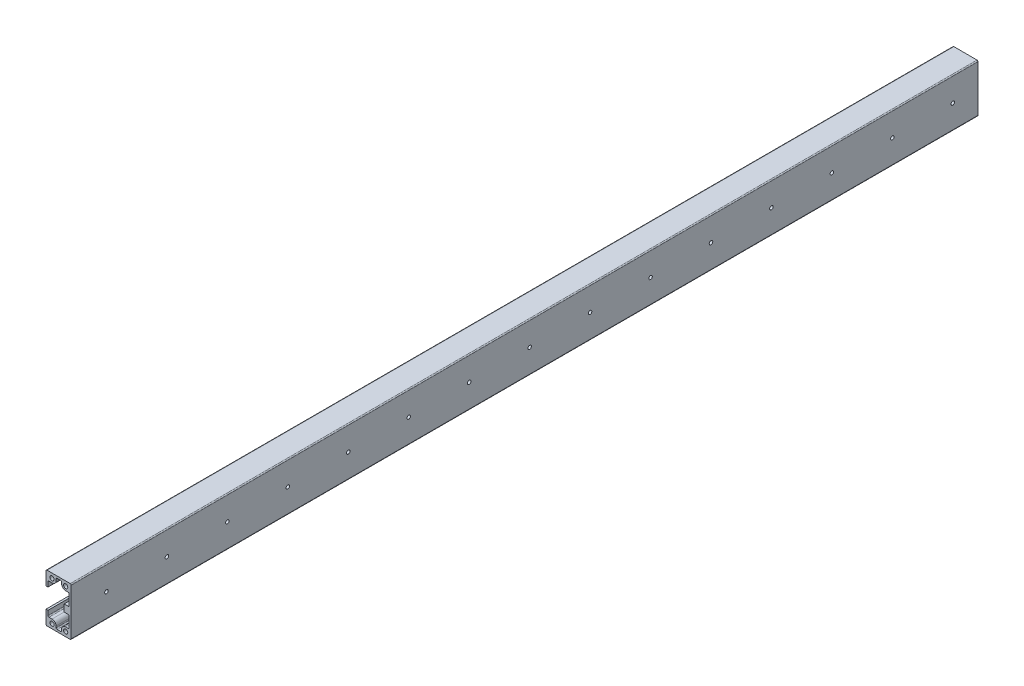
SolidWorks part; units mm, degrees
ref_plane "前视基准面" through (0, 0, 0) normal (0, 0, 1) x (1, 0, 0)
ref_plane "上视基准面" through (0, 0, 0) normal (0, 1, 0) x (1, 0, 0)
ref_plane "右视基准面" through (0, 0, 0) normal (1, 0, 0) x (0, 0, -1)
sketch "草图1" plane through (0, 0, 0) normal (0, 0, 1) x (1, 0, 0)
  line L95 (1744.9386, 1131.7125) -> (1767.9386, 1131.7125)
  line L96 (1768.9386, 1132.7125) -> (1768.9386, 1178.7125)
  line L97 (1767.9386, 1179.7125) -> (1744.9386, 1179.7125)
  line L98 (1743.9386, 1132.7125) -> (1743.9386, 1178.7125)
  line L99 (1754.9386, 1133.7125) -> (1758.4386, 1133.7125)
  line L100 (1745.9386, 1141.2125) -> (1745.9386, 1170.2125)
  line L101 (1766.9386, 1140.2125) -> (1766.9386, 1151.2125)
  line L102 (1765.9386, 1152.2125) -> (1761.9386, 1152.2125)
  line L103 (1765.9386, 1159.2125) -> (1761.9386, 1159.2125)
  line L104 (1761.9386, 1152.2125) -> (1761.9386, 1159.2125)
  line L105 (1766.9386, 1160.2125) -> (1766.9386, 1171.2125)
  line L106 (1758.4386, 1177.7125) -> (1754.9386, 1177.7125)
  line L107 (1749.9386, 1171.2125) -> (1746.9386, 1171.2125)
  line L108 (1749.9386, 1140.2125) -> (1746.9386, 1140.2125)
  line L109 (1759.4386, 1175.2125) -> (1759.4386, 1176.7125)
  line L110 (1759.4386, 1136.2125) -> (1759.4386, 1134.7125)
  line L111 (1753.9386, 1136.2125) -> (1753.9386, 1134.7125)
  line L112 (1753.9386, 1175.2125) -> (1753.9386, 1176.7125)
  line L113 (1746.7187, 1136.2125) -> (1753.049, 1136.2125) construction
  line L114 (1749.9386, 1133.1386) -> (1749.9386, 1139.2351) construction
  line L115 (1763.4386, 1133.1386) -> (1763.4386, 1139.2351) construction
  line L116 (1760.2187, 1136.2125) -> (1766.549, 1136.2125) construction
  line L117 (1763.4386, 1172.1386) -> (1763.4386, 1178.2351) construction
  line L118 (1760.2187, 1175.2125) -> (1766.549, 1175.2125) construction
  line L119 (1749.9386, 1172.1386) -> (1749.9386, 1178.2351) construction
  line L120 (1746.7187, 1175.2125) -> (1753.049, 1175.2125) construction
  line L123 (1735.6065, 1155.7125) -> (1775.0675, 1155.7125) construction
  line L128 (1763.4386, 1171.2125) -> (1766.9386, 1171.2125)
  line L129 (1763.4386, 1140.2125) -> (1766.9386, 1140.2125)
  circle A15 centre (1749.9386, 1175.2125) radius 2.1
  circle A18 centre (1763.4386, 1175.2125) radius 2.1
  circle A20 centre (1749.9386, 1136.2125) radius 2.1
  circle A21 centre (1763.4386, 1136.2125) radius 2.1
  arc A23 (1753.9386, 1136.2125) -> (1749.9386, 1140.2125) centre (1749.9386, 1136.2125) ccw
  arc A24 (1763.4386, 1140.2125) -> (1759.4386, 1136.2125) centre (1763.4386, 1136.2125) ccw
  arc A25 (1749.9386, 1171.2125) -> (1753.9386, 1175.2125) centre (1749.9386, 1175.2125) ccw
  arc A26 (1759.4386, 1175.2125) -> (1763.4386, 1171.2125) centre (1763.4386, 1175.2125) ccw
  arc A27 (1753.9386, 1134.7125) -> (1754.9386, 1133.7125) centre (1754.9386, 1134.7125) ccw
  arc A28 (1758.4386, 1133.7125) -> (1759.4386, 1134.7125) centre (1758.4386, 1134.7125) ccw
  arc A29 (1765.9386, 1159.2125) -> (1766.9386, 1160.2125) centre (1765.9386, 1160.2125) ccw
  arc A30 (1766.9386, 1151.2125) -> (1765.9386, 1152.2125) centre (1765.9386, 1151.2125) ccw
  arc A31 (1754.9386, 1177.7125) -> (1753.9386, 1176.7125) centre (1754.9386, 1176.7125) ccw
  arc A32 (1759.4386, 1176.7125) -> (1758.4386, 1177.7125) centre (1758.4386, 1176.7125) ccw
  arc A33 (1746.9386, 1171.2125) -> (1745.9386, 1170.2125) centre (1746.9386, 1170.2125) ccw
  arc A34 (1745.9386, 1141.2125) -> (1746.9386, 1140.2125) centre (1746.9386, 1141.2125) ccw
  arc A35 (1743.9386, 1132.7125) -> (1744.9386, 1131.7125) centre (1744.9386, 1132.7125) ccw
  arc A36 (1767.9386, 1131.7125) -> (1768.9386, 1132.7125) centre (1767.9386, 1132.7125) ccw
  arc A37 (1768.9386, 1178.7125) -> (1767.9386, 1179.7125) centre (1767.9386, 1178.7125) ccw
  arc A38 (1744.9386, 1179.7125) -> (1743.9386, 1178.7125) centre (1744.9386, 1178.7125) ccw
extrude "拉伸1" add sketch "草图1" along normal blind 900
sketch "草图2" plane through (1743.9386, 0, 0) normal (-1, 0, 0) x (0, 0, 1)
  line L0 (900, 1178.7125) -> (900, 1132.7125) construction
  line L1 (900, 1131.7125) -> (0, 1131.7125) construction
  line L5 (900, 1165.7125) -> (850, 1165.7125)
  line L6 (900, 1165.7125) -> (900, 1145.7125)
  line L7 (900, 1145.7125) -> (850, 1145.7125)
  arc A0 (850, 1165.7125) -> (850, 1145.7125) centre (850, 1155.7125) ccw
  dimension "D1" = 20
  dimension "D2" = 50
  dimension "D3" = 0
  dimension "D4" = 14
extrude "拉伸2" cut sketch "草图2" against normal up to next
sketch "草图3" plane through (1768.9386, 0, 0) normal (1, 0, 0) x (0, 0, -1)
  line L0 (-932.59, 1155.7125) -> (-9.4339, 1155.7125) construction
  line L1 (-900, 1132.7125) -> (-900, 1178.7125) construction
  line L2 (0, 1132.7125) -> (0, 1178.7125) construction
  circle A0 centre (-865, 1155.7125) radius 1.75
  circle A1 centre (-805, 1155.7125) radius 1.75
  circle A2 centre (-745, 1155.7125) radius 1.75
  circle A3 centre (-685, 1155.7125) radius 1.75
  circle A4 centre (-625, 1155.7125) radius 1.75
  circle A5 centre (-565, 1155.7125) radius 1.75
  circle A6 centre (-505, 1155.7125) radius 1.75
  circle A7 centre (-445, 1155.7125) radius 1.75
  circle A8 centre (-385, 1155.7125) radius 1.75
  circle A9 centre (-325, 1155.7125) radius 1.75
  circle A10 centre (-265, 1155.7125) radius 1.75
  circle A11 centre (-205, 1155.7125) radius 1.75
  circle A12 centre (-145, 1155.7125) radius 1.75
  circle A13 centre (-85, 1155.7125) radius 1.75
  circle A14 centre (-25, 1155.7125) radius 1.75
  dimension "D1" = 3.5
  dimension "D2" = 35
  dimension "D4" = 25
  dimension "D5" = 3.5
  dimension "D3" = 14
extrude "拉伸3" cut sketch "草图3" against normal up to next
hole_wizard "M5 螺纹孔1" positions "草图5" profile "草图4" tap size "M5" standard "ISO"
sketch "草图5" plane through (1743.9386, 0, 0) normal (-1, 0, 0) x (0, 0, 1)
  line L0 (900, 1131.7125) -> (0, 1131.7125) construction
  line L1 (0, 1178.7125) -> (0, 1132.7125) construction
  point P0 (44.5, 1136.7125)
  point P1 (70.5, 1136.7125)
  point P3 (96.5, 1136.7125)
  point P5 (122.5, 1136.7125)
  dimension "D1" = 5
  dimension "D2" = 44.5
  dimension "D3" = 26
  dimension "D4" = 26
  dimension "D5" = 26
sketch "草图4" plane through (1743.9386, 1136.7125, 44.5) normal (0, 1, 0) x (0, 0, 1)
  line L0 (0, 0) -> (0, 13.6618)
  line L1 (0, 13.6618) -> (2.1, 12.4)
  line L2 (2.1, 12.4) -> (2.1, 0)
  line L5 (2.1, 0) -> (0, 0)
  line L10 (0, 13.6618) -> (-2.1, 12.4) construction
  line L11 (0, -6.35) -> (0, 107.95) construction
  dimension "螺纹孔钻头直径" = 4.2
  dimension "螺纹孔钻头深度" = 12.4
  dimension "导头角度" = 118
cosmetic thread "孔螺蚊线1"
cosmetic thread "孔螺蚊线2"
cosmetic thread "孔螺蚊线3"
cosmetic thread "孔螺蚊线4"
sketch "草图6" plane through (1743.9386, 0, 0) normal (-1, 0, 0) x (0, 0, 1)
  line L0 (115, 1155.3537) -> (165, 1155.3537) construction
  line L1 (115, 1166.3537) -> (165, 1166.3537)
  line L2 (115, 1144.3537) -> (165, 1144.3537)
  line L3 (0, 1178.7125) -> (0, 1132.7125) construction
  arc A0 (115, 1166.3537) -> (115, 1144.3537) centre (115, 1155.3537) ccw
  arc A1 (165, 1144.3537) -> (165, 1166.3537) centre (165, 1155.3537) ccw
  point P2 (140, 1155.3537)
  dimension "D1" = 115
  dimension "D2" = 50
  dimension "D3" = 22
extrude "切除-拉伸1" cut sketch "草图6" against normal blind 10
